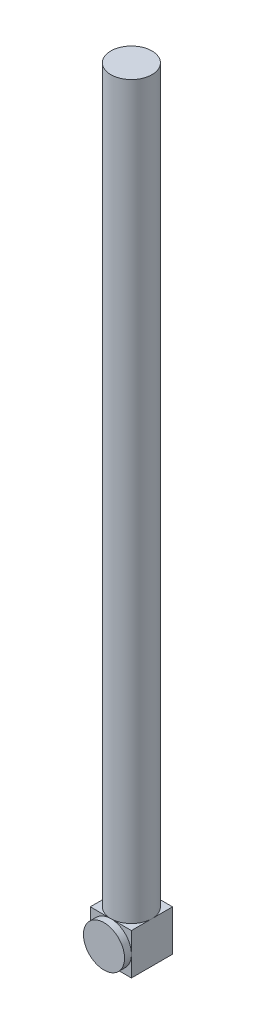
SolidWorks part; units mm, degrees
ref_plane "Front Plane" through (0, 0, 0) normal (0, 0, 1) x (1, 0, 0)
ref_plane "Top Plane" through (0, 0, 0) normal (0, 1, 0) x (1, 0, 0)
ref_plane "Right Plane" through (0, 0, 0) normal (1, 0, 0) x (0, 0, -1)
sketch "Sketch1" plane through (0, 0, 0) normal (0, 1, 0) x (1, 0, 0)
  circle A0 centre (0, 0) radius 7.5
  dimension "D1" = 15
extrude "Boss-Extrude1" add sketch "Sketch1" along normal blind 266.7
sketch "Sketch2" plane through (0, 0, 0) normal (0, -1, 0) x (1, 0, 0)
  line L1 (-7.5, 7.5) -> (7.5, 7.5)
  line L2 (-7.5, 7.5) -> (-7.5, -7.5)
  line L3 (-7.5, -7.5) -> (7.5, -7.5)
  line L4 (7.5, 7.5) -> (7.5, -7.5)
  circle A1 centre (0, 0) radius 7.5
  circle A2 centre (0, 0) radius 7.5
  circle M2 centre (0, 0) radius 7.5
  dimension "D1" = 0
extrude "Boss-Extrude2" add sketch "Sketch2" along normal blind 15 contours L1 L2 M2 | M2 | L4 L1 M2 | L4 L3 M2 | L2 L3 M2
sketch "Sketch3" plane through (0, 0, 7.5) normal (0, 0, 1) x (1, 0, 0)
  line L2 (0, 0) -> (7.5, 0) construction
  line L3 (7.5, -15) -> (7.5, 0) construction
  line L4 (-7.5, -15) -> (7.5, -15) construction
  circle A0 centre (0, -7.5) radius 7.5
extrude "Boss-Extrude3" add sketch "Sketch3" along normal blind 2.5
